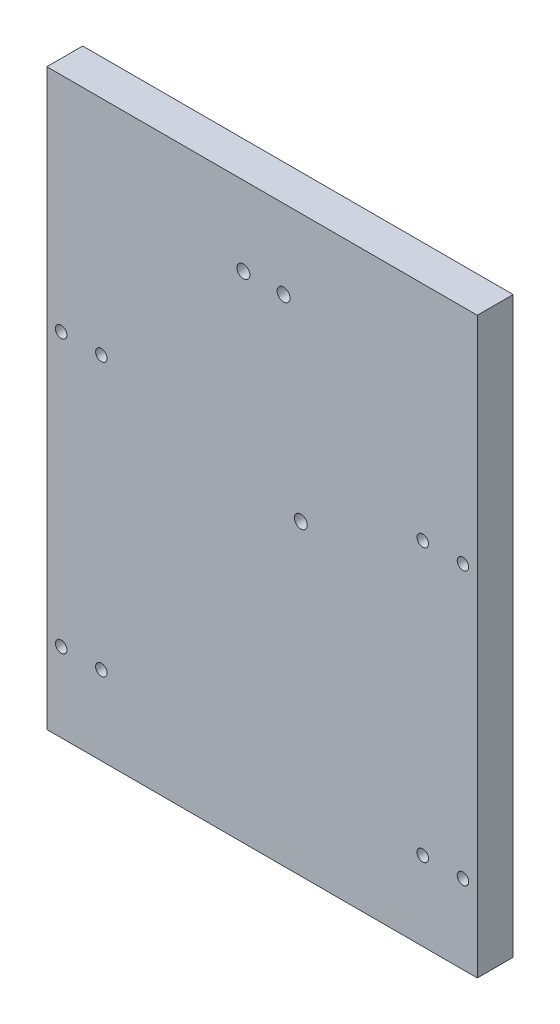
SolidWorks part; units mm, degrees
material "Balsa"
ref_plane "Front" through (0, 0, 0) normal (0, 0, 1) x (1, 0, 0)
ref_plane "Top" through (0, 0, 0) normal (0, 1, 0) x (1, 0, 0)
ref_plane "Right" through (0, 0, 0) normal (1, 0, 0) x (0, 0, -1)
sketch "Sketch1" plane through (0, 0, 0) normal (0, 0, 1) x (1, 0, 0)
  line L0 (0, 213.5111) -> (0, -303.9575) construction
  line L1 (-150, 200) -> (150, 200)
  line L2 (-150, 200) -> (-150, -200)
  line L3 (-150, -200) -> (150, -200)
  line L4 (150, 200) -> (150, -200)
  line L5 (-150, 200) -> (150, -200) construction
  line L6 (-150, -200) -> (150, 200) construction
  line L7 (-272.6085, -50) -> (194.7551, -50) construction
  circle A0 centre (-112, -145) radius 4
  circle A1 centre (-140, -145) radius 4
  circle A2 centre (112, -145) radius 4
  circle A3 centre (140, -145) radius 4
  circle A4 centre (15, 145) radius 4.5
  circle A5 centre (-13, 145) radius 4.5
  circle A6 centre (27, 14) radius 4.5
  circle A7 centre (140, 45) radius 4
  circle A8 centre (112, 45) radius 4
  circle A9 centre (-112, 45) radius 4
  circle A10 centre (-140, 45) radius 4
  point P0 (0, 0)
  dimension "D4" = 8
  dimension "D5" = 10
  dimension "D6" = 28
  dimension "D7" = 9
  dimension "D1" = 400
  dimension "D2" = 300
  dimension "D3" = 55
  dimension "D8" = 28
  dimension "D9" = 135
  dimension "D10" = 55
  dimension "D11" = 131
  dimension "D12" = 12
  dimension "D13" = 150
extrude "Boss-Extrude1" add sketch "Sketch1" against normal blind 25
